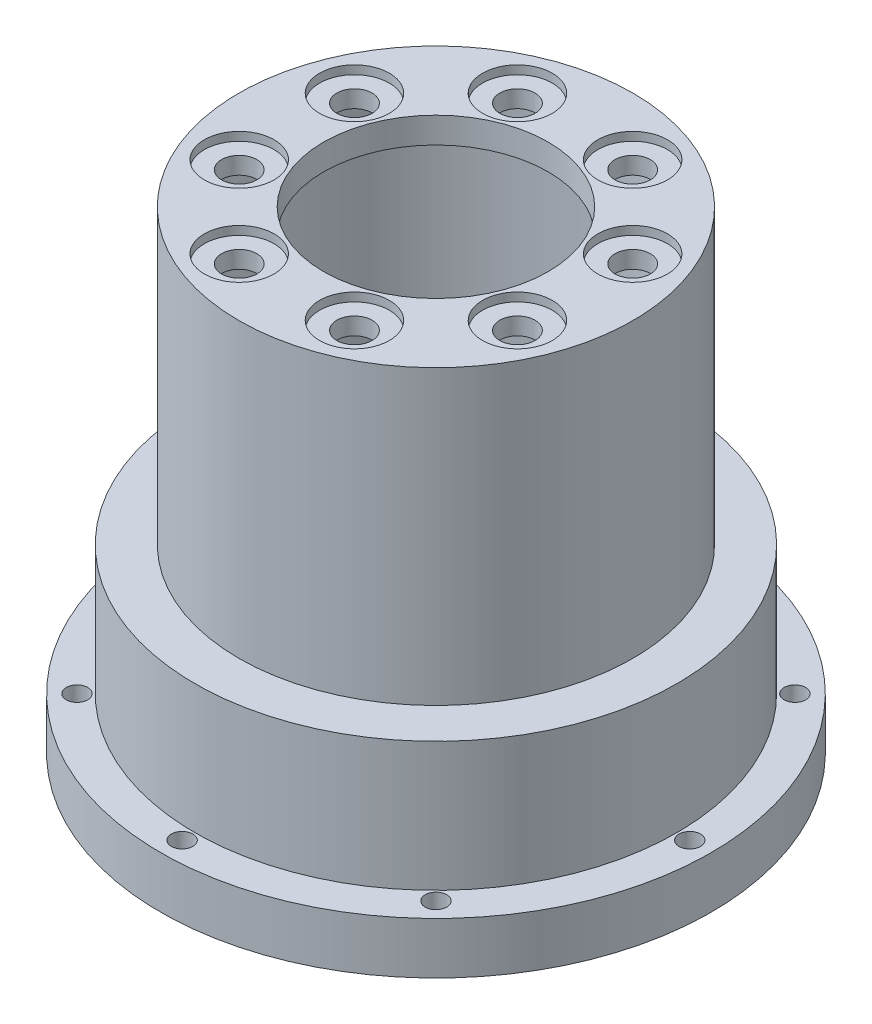
SolidWorks part; units mm, degrees
material "6061-T4 (SS)"
ref_plane "前视基准面" through (0, 0, 0) normal (0, 0, 1) x (1, 0, 0)
ref_plane "上视基准面" through (0, 0, 0) normal (0, 1, 0) x (1, 0, 0)
ref_plane "右视基准面" through (0, 0, 0) normal (1, 0, 0) x (0, 0, -1)
sketch "草图1" plane through (0, 0, 0) normal (0, 0, 1) x (1, 0, 0)
  line L0 (32, 0) -> (32, 6)
  line L1 (32, 6) -> (28, 6)
  line L2 (28, 6) -> (28, 21)
  line L3 (28, 21) -> (22.9, 21)
  line L4 (22.9, 21) -> (22.9, 55)
  line L5 (22.9, 55) -> (13.05, 55)
  line L6 (13.05, 55) -> (13.05, 52)
  line L7 (13.05, 52) -> (21.1, 52)
  line L8 (21.1, 52) -> (21.1, 18)
  line L9 (21.1, 18) -> (26, 18)
  line L10 (26, 18) -> (26, 0)
  line L11 (26, 0) -> (32, 0)
  line L12 (0, 0) -> (0, 58.9574) construction
  circle A0 centre (49, 21) radius 21 construction
  dimension "D10" = 42
  dimension "D1" = 32
  dimension "D2" = 6
  dimension "D3" = 26
  dimension "D4" = 2
  dimension "D5" = 13.05
  dimension "D6" = 21.1
  dimension "D7" = 1.8
  dimension "D8" = 3
  dimension "D9" = 18
  dimension "D11" = 55
  dimension "D12" = 3
revolve "旋转1" add sketch "草图1" angle 360 about L12
sketch "草图2" plane through (0, 0, 0) normal (0, -1, 0) x (1, 0, 0)
  circle A0 centre (0, 0) radius 29.5 construction
  dimension "D1" = 59
hole_wizard "M3 螺纹孔1" positions "草图3" profile "草图4" tap size "M3" standard "GB" end condition up to next
sketch "草图3" plane through (0, 0, 0) normal (0, -1, 0) x (-1, 0, 0)
  circle A0 centre (0, 0) radius 29.5 construction
  point P0 (0, 29.5)
  point P4 (29.5, 0)
  point P6 (0, -29.5)
  point P8 (-29.5, 0)
sketch "草图4" plane through (0, 0, -29.5) normal (1, 0, 0) x (0, 0, -1)
  line L0 (0, 0) -> (0, 6)
  line L1 (0, 6) -> (1.25, 6)
  line L2 (1.25, 6) -> (1.25, 0)
  line L5 (1.25, 0) -> (0, 0)
  line L11 (0, -6.35) -> (0, 107.95) construction
  dimension "通孔螺纹孔钻头直径" = 2.5
  dimension "通孔螺纹孔钻头深度" = 6
cosmetic thread "孔螺蚊线1" parameters "D2"=3
cosmetic thread "孔螺蚊线2" parameters "D2"=3
cosmetic thread "孔螺蚊线3" parameters "D2"=3
cosmetic thread "孔螺蚊线4" parameters "D2"=3
pattern_circular "阵列(圆周)1" count 2 over 45 about axis through (0, 0, 0) along (0, 1, 0) of "M3 螺纹孔1"
cosmetic thread "孔螺蚊线5" parameters "D2"=3
cosmetic thread "孔螺蚊线6" parameters "D2"=3
cosmetic thread "孔螺蚊线7" parameters "D2"=3
cosmetic thread "孔螺蚊线8" parameters "D2"=3
sketch "草图5" plane through (0, 55, 0) normal (0, 1, 0) x (1, 0, 0)
  line L0 (-6.697, 16.1679) -> (0, 0) construction
  line L1 (0, 0) -> (0, 17.5) construction
  circle A0 centre (0, 0) radius 17.5 construction
  circle A1 centre (-6.697, 16.1679) radius 2.05
  dimension "D1" = 35
  dimension "D2" = 4.1
  dimension "D3" = 22.5
extrude "切除-拉伸1" cut sketch "草图5" against normal blind 10
pattern_circular "阵列(圆周)2" count 8 over 360 about axis through (0, 0, 0) along (0, 1, 0) of "切除-拉伸1"
sketch "草图6" plane through (0, 55, 0) normal (0, 1, 0) x (1, 0, 0)
  circle A0 centre (-6.697, 16.1679) radius 4.05
  dimension "D1" = 8.1
extrude "切除-拉伸2" cut sketch "草图6" against normal blind 1
pattern_circular "阵列(圆周)3" count 8 over 360 about axis through (0, 0, 0) along (0, 1, 0) of "切除-拉伸2"
